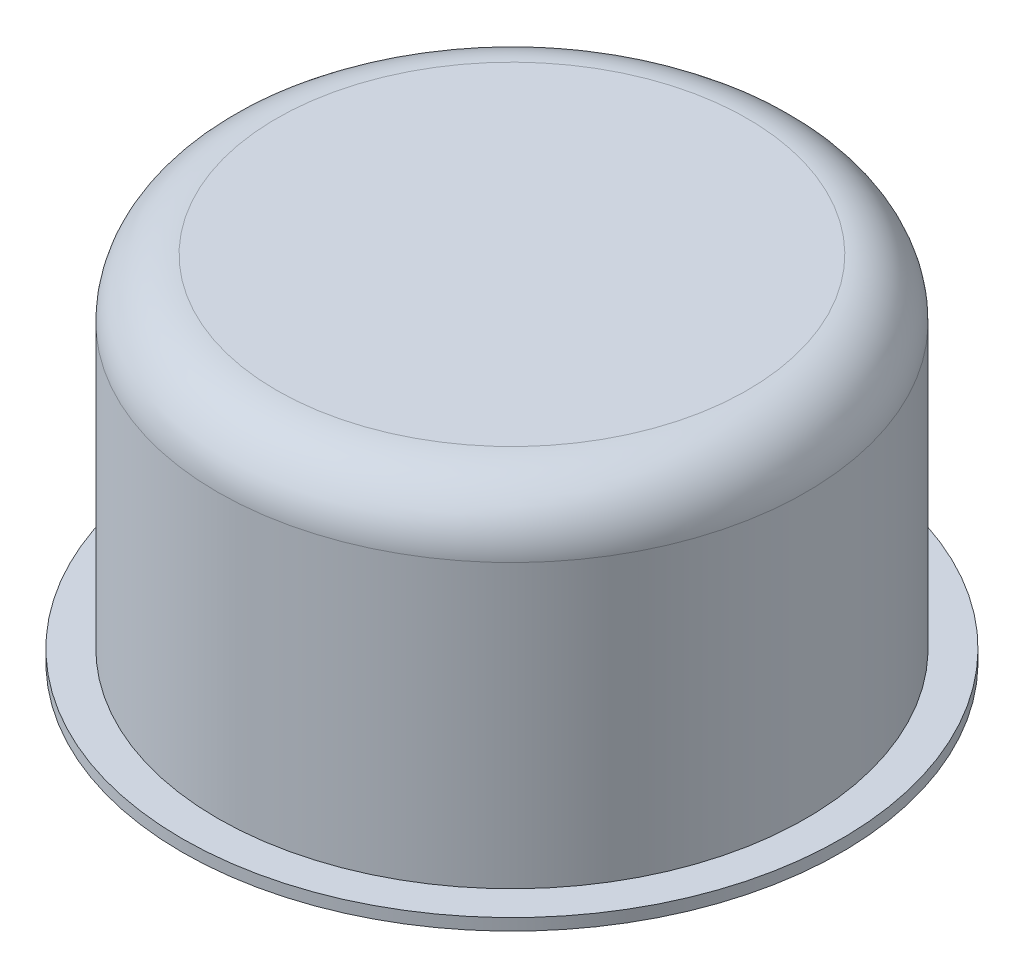
SolidWorks part; units mm, degrees
ref_plane "Front Plane" through (0, 0, 0) normal (0, 0, 1) x (1, 0, 0)
ref_plane "Top Plane" through (0, 0, 0) normal (0, 1, 0) x (1, 0, 0)
ref_plane "Right Plane" through (0, 0, 0) normal (1, 0, 0) x (0, 0, -1)
sketch "Sketch1" plane through (0, 0, 0) normal (0, 1, 0) x (1, 0, 0)
  circle A0 centre (0, 0) radius 12.5
  dimension "D1" = 25
sketch "Sketch2" plane through (0, 0, 0) normal (0, 1, 0) x (1, 0, 0)
  circle A0 centre (0, 0) radius 14
  dimension "D1" = 28
extrude "Boss-Extrude2" add sketch "Sketch1" along normal blind 15
extrude "Boss-Extrude3" add sketch "Sketch2" along normal blind 0.5
sketch "Sketch3" plane through (0, 0, 0) normal (0, 1, 0) x (1, 0, 0)
  circle A0 centre (0, 0) radius 12.25
  dimension "D1" = 24.5
extrude "Cut-Extrude1" cut sketch "Sketch3" along normal blind 14.5
fillet "Fillet1" radius 2.5 1 edges at (0, 15, 12.5)
fillet "Fillet2" radius 2.5 1 edges at (0, 14.5, 12.25)
